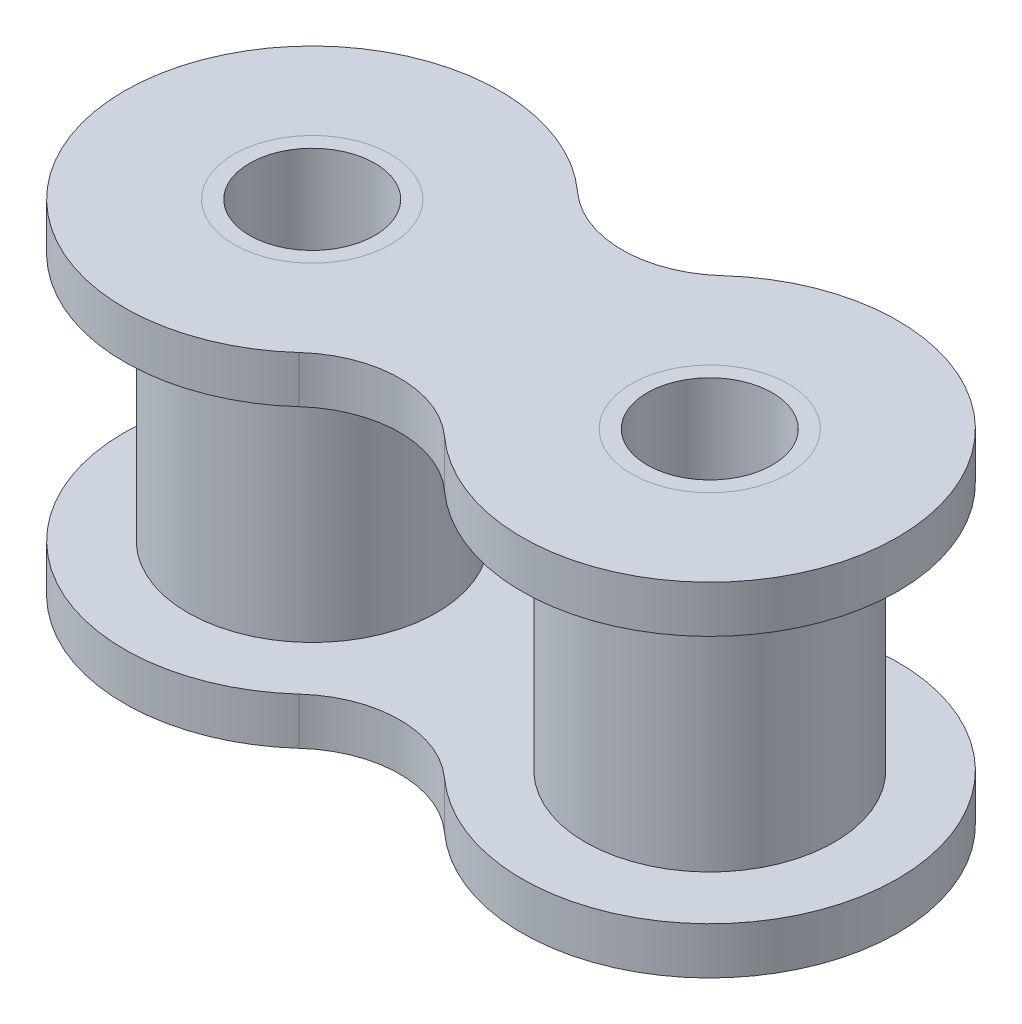
SolidWorks part; units mm, degrees
material "Aço carbono simples"
ref_plane "Plano frontal" through (0, 0, 0) normal (0, 0, 1) x (1, 0, 0)
ref_plane "Plano superior" through (0, 0, 0) normal (0, 1, 0) x (1, 0, 0)
ref_plane "Plano direito" through (0, 0, 0) normal (1, 0, 0) x (0, 0, -1)
ref_plane "Plano18" through (0, 5.475, 0) normal (0, 1, 0) x (1, 0, 0)
sketch "Esboço85" plane through (0, 5.475, 0) normal (0, 1, 0) x (1, 0, 0)
  circle A0 centre (6.35, 0) radius 2.5
  circle A1 centre (-6.35, 0) radius 2.5
  arc A2 (2.32, 4.4451) -> (-2.32, 4.4451) centre (0, 7.0041) cw
  arc A3 (-2.32, 4.4451) -> (-2.32, -4.4451) centre (-6.35, 0) ccw
  arc A4 (-2.32, -4.4451) -> (2.32, -4.4451) centre (0, -7.0041) cw
  arc A5 (2.32, -4.4451) -> (2.32, 4.4451) centre (6.35, 0) ccw
extrude "Ressalto-extrusão9" add sketch "Esboço85" against normal blind 1.5 separate body
ref_plane "Plano19" through (0, -5.475, 0) normal (0, -1, 0) x (-1, 0, 0)
sketch "Esboço90" plane through (0, -5.475, 0) normal (0, -1, 0) x (-1, 0, 0)
  circle A0 centre (-6.35, 0) radius 2.5
  circle A1 centre (6.35, 0) radius 2.5
  arc A2 (2.32, 4.4451) -> (-2.32, 4.4451) centre (0, 7.0041) cw
  arc A3 (-2.32, 4.4451) -> (-2.32, -4.4451) centre (-6.35, 0) ccw
  arc A4 (-2.32, -4.4451) -> (2.32, -4.4451) centre (0, -7.0041) cw
  arc A5 (2.32, -4.4451) -> (2.32, 4.4451) centre (6.35, 0) ccw
extrude "Ressalto-extrusão10" add sketch "Esboço90" against normal blind 1.5 separate body
ref_plane "Plano20" through (0, 0, 0) normal (0, 0, -1) x (-1, 0, 0)
sketch "Esboço96" plane through (0, 0, 0) normal (0, 0, -1) x (-1, 0, 0)
  line L0 (2.375, 3.975) -> (2.375, -3.975)
  line L1 (2.375, -3.975) -> (3.85, -3.975)
  line L2 (3.85, -3.975) -> (3.85, 3.975)
  line L3 (3.85, 3.975) -> (2.375, 3.975)
  line L4 (6.35, -3.975) -> (6.35, 3.975) construction
revolve "Revolução13" add sketch "Esboço96" angle 360 about L4
sketch "Esboço103" plane through (0, 0, 0) normal (0, 0, -1) x (-1, 0, 0)
  line L0 (-10.325, -3.975) -> (-8.85, -3.975)
  line L1 (-8.85, -3.975) -> (-8.85, 3.975)
  line L2 (-8.85, 3.975) -> (-10.325, 3.975)
  line L3 (-10.325, 3.975) -> (-10.325, -3.975)
  line L4 (-6.35, -3.975) -> (-6.35, 3.975) construction
revolve "Revolução14" add sketch "Esboço103" angle 360 about L4
sketch "Esboço110" plane through (0, 0, 0) normal (0, 0, -1) x (-1, 0, 0)
  line L0 (3.85, 5.475) -> (3.85, -5.475)
  line L1 (3.85, -5.475) -> (4.35, -5.475)
  line L2 (4.35, -5.475) -> (4.35, 5.475)
  line L3 (4.35, 5.475) -> (3.85, 5.475)
  line L4 (6.35, -5.475) -> (6.35, 5.475) construction
revolve "Revolução15" add sketch "Esboço110" angle 360 about L4
sketch "Esboço117" plane through (0, 0, 0) normal (0, 0, -1) x (-1, 0, 0)
  line L0 (-8.85, 5.475) -> (-8.85, -5.475)
  line L1 (-8.85, -5.475) -> (-8.35, -5.475)
  line L2 (-8.35, -5.475) -> (-8.35, 5.475)
  line L3 (-8.35, 5.475) -> (-8.85, 5.475)
  line L4 (-6.35, -5.475) -> (-6.35, 5.475) construction
revolve "Revolução16" add sketch "Esboço117" angle 360 about L4
